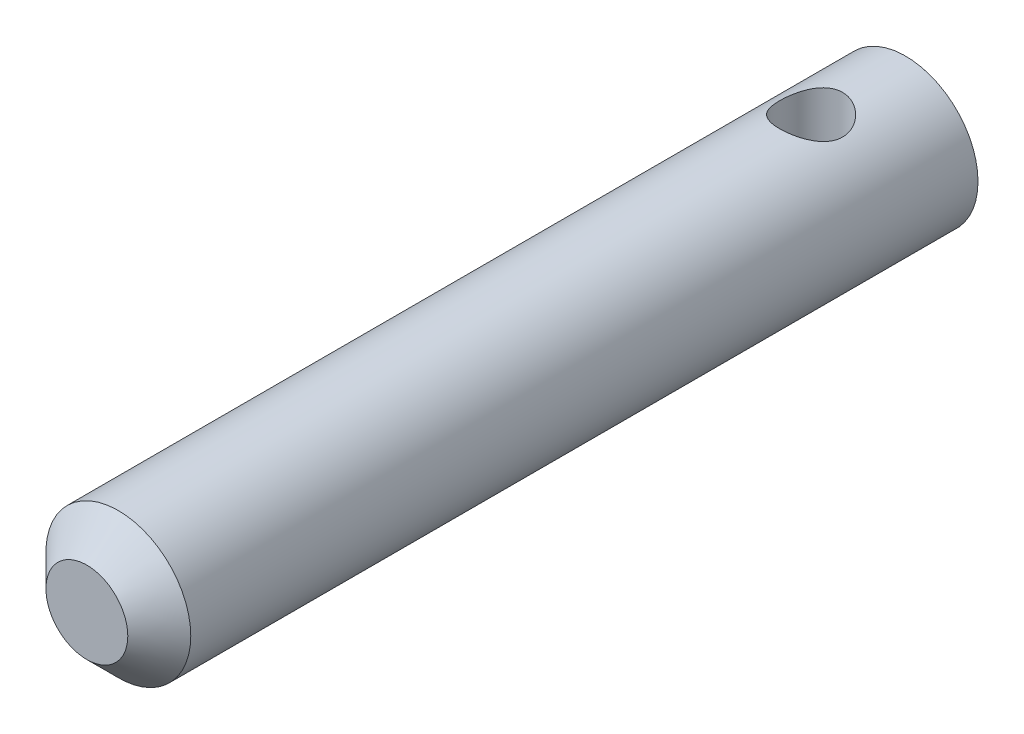
SolidWorks part; units mm, degrees
ref_plane "Front Plane" through (0, 0, 0) normal (0, 0, 1) x (1, 0, 0)
ref_plane "Top Plane" through (0, 0, 0) normal (0, 1, 0) x (1, 0, 0)
ref_plane "Right Plane" through (0, 0, 0) normal (1, 0, 0) x (0, 0, -1)
sketch "Sketch1" plane through (0, 0, 0) normal (0, 0, 1) x (1, 0, 0)
  circle A0 centre (0, 0) radius 11.5
  dimension "D1" = 23
extrude "Boss-Extrude1" add sketch "Sketch1" along normal blind 130 contours A0
chamfer "Chamfer1" distance 5 angle 45 1 edges at (11.5, 0, 130)
sketch "Sketch2" plane through (0, 0, 0) normal (0, 1, 0) x (1, 0, 0)
  line L0 (11.5, 0) -> (-11.5, 0) construction
  line L1 (11.5, -125) -> (11.5, 0) construction
  circle A0 centre (0, -15) radius 5
  dimension "D1" = 10
  dimension "D3" = 11.5
  dimension "D2" = 15
extrude "Cut-Extrude1" cut sketch "Sketch2" against normal through all both and the other way through all
